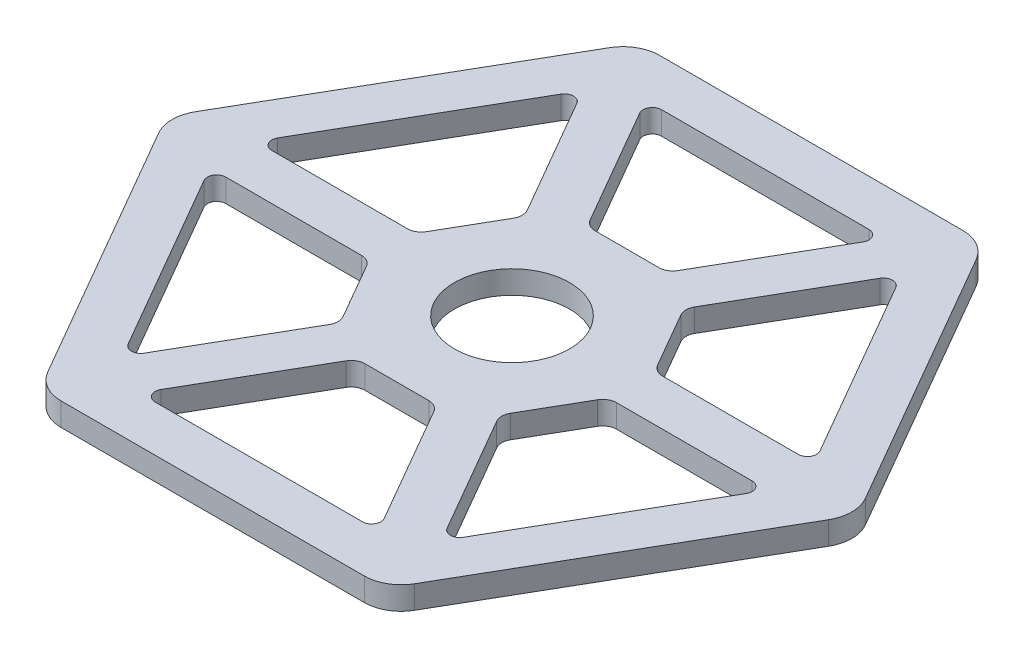
SolidWorks part; units mm, degrees
ref_plane "Front Plane" through (0, 0, 0) normal (0, 0, 1) x (1, 0, 0)
ref_plane "Top Plane" through (0, 0, 0) normal (0, 1, 0) x (1, 0, 0)
ref_plane "Right Plane" through (0, 0, 0) normal (1, 0, 0) x (0, 0, -1)
sketch "Sketch1" plane through (0, 0, 0) normal (0, 1, 0) x (1, 0, 0)
  line L1 (-75.0555, 0) -> (-37.5278, -65)
  line L2 (-37.5278, -65) -> (37.5278, -65)
  line L3 (37.5278, -65) -> (75.0555, 0)
  line L4 (75.0555, 0) -> (37.5278, 65)
  line L5 (37.5278, 65) -> (-37.5278, 65)
  line L6 (-37.5278, 65) -> (-75.0555, 0)
  circle A0 centre (0, 0) radius 65 construction
  circle A1 centre (0, 0) radius 50 construction
  dimension "D2" = 100
  dimension "D1" = 130
extrude "Boss-Extrude1" add sketch "Sketch1" along normal blind 5
fillet "Fillet1" radius 8 6 edges at (37.5278, 2.5, -65) (75.0555, 2.5, 0) (37.5278, 2.5, 65) (-37.5278, 2.5, 65) (-75.0555, 2.5, 0) (-37.5278, 2.5, -65)
sketch "Sketch2" plane through (0, 5, 0) normal (0, 1, 0) x (1, 0, 0)
  line L0 (0, 40) -> (0, 25) construction
  line L1 (0, 55) -> (0, 65) construction
  line L2 (9.5263, 26.5) -> (24.2487, 52)
  line L3 (22.5167, 55) -> (-22.5167, 55)
  line L4 (-24.2487, 52) -> (-9.5263, 26.5)
  line L5 (32.909, 65) -> (-32.909, 65) construction
  line L36 (6.9282, 25) -> (-6.9282, 25)
  line L37 (27.7128, 5) -> (57.1577, 5)
  line L38 (58.8897, 8) -> (36.3731, 47)
  line L39 (32.909, 47) -> (18.1865, 21.5)
  line L40 (25.1147, 6.5) -> (18.1865, 18.5)
  line L41 (18.1865, -21.5) -> (32.909, -47)
  line L42 (36.3731, -47) -> (58.8897, -8)
  line L43 (57.1577, -5) -> (27.7128, -5)
  line L44 (18.1865, -18.5) -> (25.1147, -6.5)
  line L45 (-9.5263, -26.5) -> (-24.2487, -52)
  line L46 (-22.5167, -55) -> (22.5167, -55)
  line L47 (24.2487, -52) -> (9.5263, -26.5)
  line L48 (-6.9282, -25) -> (6.9282, -25)
  line L49 (-27.7128, -5) -> (-57.1577, -5)
  line L50 (-58.8897, -8) -> (-36.3731, -47)
  line L51 (-32.909, -47) -> (-18.1865, -21.5)
  line L52 (-25.1147, -6.5) -> (-18.1865, -18.5)
  line L53 (-18.1865, 21.5) -> (-32.909, 47)
  line L54 (-36.3731, 47) -> (-58.8897, 8)
  line L55 (-57.1577, 5) -> (-27.7128, 5)
  line L56 (-18.1865, 18.5) -> (-25.1147, 6.5)
  circle A0 centre (0, 0) radius 12.5
  circle A1 centre (0, 40) radius 15 construction
  arc A3 (-22.5167, 55) -> (-24.2487, 52) centre (-22.5167, 53) ccw
  arc A4 (24.2487, 52) -> (22.5167, 55) centre (22.5167, 53) ccw
  arc A5 (6.9282, 25) -> (9.5263, 26.5) centre (6.9282, 28) ccw
  arc A6 (-6.9282, 25) -> (-9.5263, 26.5) centre (-6.9282, 28) cw
  arc A7 (25.1147, 6.5) -> (27.7128, 5) centre (27.7128, 8) ccw
  arc A8 (57.1577, 5) -> (58.8897, 8) centre (57.1577, 7) ccw
  arc A9 (36.3731, 47) -> (32.909, 47) centre (34.641, 46) ccw
  arc A10 (18.1865, 18.5) -> (18.1865, 21.5) centre (20.7846, 20) cw
  arc A11 (18.1865, -18.5) -> (18.1865, -21.5) centre (20.7846, -20) ccw
  arc A12 (32.909, -47) -> (36.3731, -47) centre (34.641, -46) ccw
  arc A13 (58.8897, -8) -> (57.1577, -5) centre (57.1577, -7) ccw
  arc A14 (25.1147, -6.5) -> (27.7128, -5) centre (27.7128, -8) cw
  arc A15 (-6.9282, -25) -> (-9.5263, -26.5) centre (-6.9282, -28) ccw
  arc A16 (-24.2487, -52) -> (-22.5167, -55) centre (-22.5167, -53) ccw
  arc A17 (22.5167, -55) -> (24.2487, -52) centre (22.5167, -53) ccw
  arc A18 (6.9282, -25) -> (9.5263, -26.5) centre (6.9282, -28) cw
  arc A19 (-25.1147, -6.5) -> (-27.7128, -5) centre (-27.7128, -8) ccw
  arc A20 (-57.1577, -5) -> (-58.8897, -8) centre (-57.1577, -7) ccw
  arc A21 (-36.3731, -47) -> (-32.909, -47) centre (-34.641, -46) ccw
  arc A22 (-18.1865, -18.5) -> (-18.1865, -21.5) centre (-20.7846, -20) cw
  arc A23 (-18.1865, 18.5) -> (-18.1865, 21.5) centre (-20.7846, 20) ccw
  arc A24 (-32.909, 47) -> (-36.3731, 47) centre (-34.641, 46) ccw
  arc A25 (-58.8897, 8) -> (-57.1577, 5) centre (-57.1577, 7) ccw
  arc A26 (-25.1147, 6.5) -> (-27.7128, 5) centre (-27.7128, 8) cw
  point P19 (0, 25)
  point P30 (0, 0)
  point P66 (0, 0)
  point P88 (0, 0)
  dimension "D1" = 25
  dimension "D3" = 30
  dimension "D6" = 2
  dimension "D8" = 3
  dimension "D2" = 40
  dimension "D4" = 10
  dimension "D5" = 15
  dimension "D7" = 25
extrude "Cut-Extrude1" cut sketch "Sketch2" against normal blind 10
